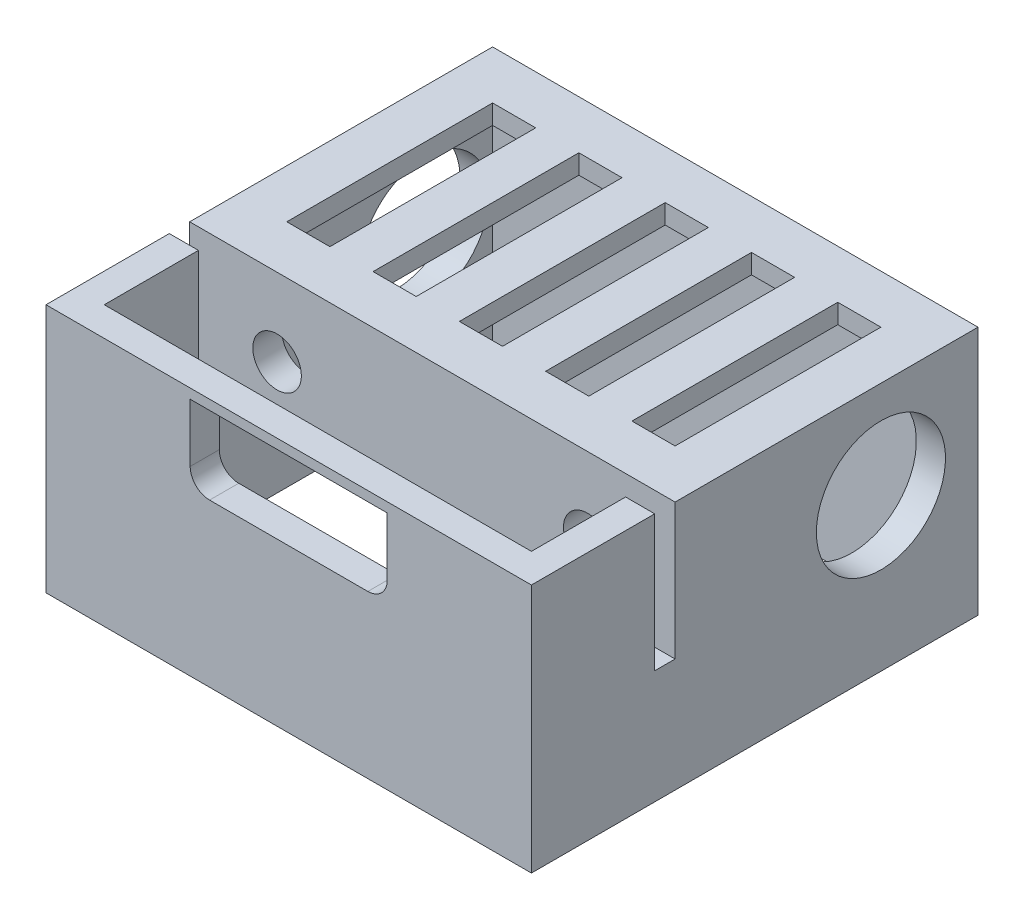
SolidWorks part; units mm, degrees
ref_plane "Alzado" through (0, 0, 0) normal (0, 0, 1) x (1, 0, 0)
ref_plane "Planta" through (0, 0, 0) normal (0, 1, 0) x (1, 0, 0)
ref_plane "Vista lateral" through (0, 0, 0) normal (1, 0, 0) x (0, 0, -1)
sketch "Croquis1" plane through (0, 0, 0) normal (0, 1, 0) x (1, 0, 0)
  line L0 (3, 3) -> (-47, 3)
  line L1 (0, 0) -> (-44, 0)
  line L2 (0, 0) -> (0, -40)
  line L3 (0, -40) -> (-44, -40)
  line L4 (-44, 0) -> (-44, -40)
  line L5 (-47, 3) -> (-47, -43)
  line L6 (3, -43) -> (-47, -43)
  line L7 (3, 3) -> (3, -43)
  dimension "D1" = 44
  dimension "D2" = 40
  dimension "D3" = 3
extrude "Saliente-Extruir1" add sketch "Croquis1" along normal blind 15
sketch "Croquis4" plane through (0, 15, 0) normal (0, 1, 0) x (1, 0, 0)
  line L0 (-47, -43) -> (3, -43) construction
  line L1 (-44, -40) -> (0, -40)
  line L2 (-44, -40) -> (-44, -43)
  line L3 (-44, -43) -> (0, -43)
  line L4 (0, -40) -> (0, -43)
extrude "Saliente-Extruir3" add sketch "Croquis4" along normal blind 10.7
sketch "Croquis6" plane through (0, 0, 43) normal (0, 0, 1) x (1, 0, 0)
  line L0 (-22, 25.7) -> (-22, 24.7) construction
  line L1 (-44, 25.7) -> (0, 25.7) construction
  line L2 (-22, 24.7) -> (-11.85, 24.7)
  line L3 (-11.85, 24.7) -> (-11.85, 16.7)
  line L4 (-11.85, 16.7) -> (-32.15, 16.7)
  line L5 (-32.15, 16.7) -> (-32.15, 24.7)
  line L6 (-32.15, 24.7) -> (-22, 24.7)
  dimension "D1" = 1
  dimension "D2" = 10.15
  dimension "D3" = 10.15
  dimension "D4" = 8
extrude "Cortar-Extruir1" cut sketch "Croquis6" against normal up to next
sketch "Croquis7" plane through (0, 0, 43) normal (0, 0, 1) x (1, 0, 0)
  line L0 (-22, 25.7) -> (-22, 19.9995) construction
  line L1 (-47, 15) -> (-44, 15)
  line L2 (-47, 15) -> (-47, 25.7)
  line L3 (-47, 25.7) -> (-44, 25.7)
  line L4 (-44, 15) -> (-44, 25.7)
  line L5 (-44, 25.7) -> (0, 25.7) construction
  line L6 (0, 15) -> (0, 25.7)
  line L7 (3, 25.7) -> (0, 25.7)
  line L8 (3, 15) -> (3, 25.7)
  line L9 (3, 15) -> (0, 15)
extrude "Saliente-Extruir4" add sketch "Croquis7" against normal blind 10.7
sketch "Croquis8" plane through (0, 15, 0) normal (0, 1, 0) x (1, 0, 0)
  line L0 (-45.5, -32.3) -> (-45.5, -28.2) construction
  line L1 (-47, -28.2) -> (-44, -28.2)
  line L2 (0, -28.2) -> (3, -28.2)
  line L3 (-47, -32.3) -> (-44, -32.3) construction
  line L4 (1.5, -28.2) -> (1.5, -32.3) construction
  line L5 (0, -32.3) -> (3, -32.3) construction
  line L8 (0, 0) -> (0, -32.3)
  line L9 (0, -32.3) -> (3, -32.3)
  line L10 (3, -32.3) -> (3, 3)
  line L11 (3, 3) -> (-47, 3)
  line L12 (-47, 3) -> (-47, -32.3)
  line L13 (-47, -32.3) -> (-44, -32.3)
  line L14 (-44, -32.3) -> (-44, 0)
  line L15 (-44, 0) -> (0, 0)
  line L16 (0, 0) -> (0, -28.2)
  line L18 (3, -28.2) -> (3, 3)
  line L19 (3, 3) -> (-47, 3)
  line L20 (-47, 3) -> (-47, -28.2)
  line L22 (-44, -28.2) -> (-44, 0)
  line L23 (-44, 0) -> (0, 0)
  dimension "D2" = 4.1
  dimension "D3" = 4.1
  dimension "D1" = 0
extrude "Saliente-Extruir5" add sketch "Croquis8" along normal blind 10.7
sketch "Croquis9" plane through (-47, 0, 0) normal (-1, 0, 0) x (0, 0, 1)
  line L0 (-3, 15.7) -> (7, 15.7) construction
  line L1 (-3, 25.7) -> (-3, 0) construction
  line L2 (7, 15.7) -> (7, 25.7) construction
  line L3 (-3, 25.7) -> (28.2, 25.7) construction
  circle A0 centre (7, 15.7) radius 6.65
  dimension "D1" = 13.3
  dimension "D2" = 10
  dimension "D3" = 10
extrude "Cortar-Extruir2" cut sketch "Croquis9" against normal up to next
sketch "Croquis10" plane through (0, 0, 0) normal (-1, 0, 0) x (0, 0, 1)
  circle A0 centre (7, 15.7) radius 6.65 construction
  circle A1 centre (7, 15.7) radius 6.65
extrude "Cortar-Extruir3" cut sketch "Croquis10" against normal up to next
sketch "Croquis11" plane through (0, 25.7, 0) normal (0, 1, 0) x (1, 0, 0)
  line L0 (-47, 3) -> (-47, -28.2)
  line L1 (-47, 3) -> (3, 3)
  line L5 (-47, 3) -> (-47, -28.2) construction
  line L6 (-47, -28.2) -> (3, -28.2)
  line L7 (3, -28.2) -> (3, 3) construction
  line L8 (3, -28.2) -> (3, 3)
  dimension "D1" = 31.2
extrude "Saliente-Extruir6" add sketch "Croquis11" against normal blind 2
sketch "Croquis12" plane through (0, 0, 0) normal (-1, 0, 0) x (0, 0, 1)
  line L1 (28.2, 23.7) -> (25.2, 23.7)
  line L2 (28.2, 23.7) -> (28.2, 11.7)
  line L3 (28.2, 11.7) -> (25.2, 11.7)
  line L4 (25.2, 23.7) -> (25.2, 11.7)
  dimension "D1" = 3
  dimension "D2" = 12
extrude "Saliente-Extruir7" add sketch "Croquis12" along normal up to surface (44 mm away) up to face at (-44, 15.7, 0.35)
sketch "Croquis13" plane through (0, 0, 25.2) normal (0, 0, -1) x (-1, 0, 0)
  line L0 (0, 17.7) -> (6, 17.7) construction
  line L1 (0, 23.7) -> (0, 11.7) construction
  line L2 (22, 11.7) -> (22, 18.7495) construction
  line L3 (44, 11.7) -> (0, 11.7) construction
  line L4 (6, 17.7) -> (6, 23.7) construction
  line L5 (44, 23.7) -> (0, 23.7) construction
  circle A0 centre (6, 17.7) radius 2.5
  circle A1 centre (38, 17.7) radius 2.5
  dimension "D2" = 5
  dimension "D1" = 6
extrude "Cortar-Extruir4" cut sketch "Croquis13" against normal up to next
sketch "Croquis14" plane through (0, 0, 25.2) normal (0, 0, -1) x (-1, 0, 0)
  line L0 (44, 17.7) -> (38, 17.7) construction
  line L1 (44, 11.7) -> (44, 23.7) construction
  line L2 (22, 11.7) -> (22, 15.4) construction
  line L3 (43.3116, 17.7) -> (40.6558, 22.3)
  line L4 (40.6558, 22.3) -> (35.3442, 22.3)
  line L5 (35.3442, 22.3) -> (32.6884, 17.7)
  line L6 (32.6884, 17.7) -> (35.3442, 13.1)
  line L7 (35.3442, 13.1) -> (40.6558, 13.1)
  line L8 (40.6558, 13.1) -> (43.3116, 17.7)
  line L9 (44, 11.7) -> (0, 11.7) construction
  line L10 (3.3442, 13.1) -> (0.6884, 17.7)
  line L11 (8.6558, 13.1) -> (3.3442, 13.1)
  line L12 (11.3116, 17.7) -> (8.6558, 13.1)
  line L13 (8.6558, 22.3) -> (11.3116, 17.7)
  line L14 (3.3442, 22.3) -> (8.6558, 22.3)
  line L15 (0.6884, 17.7) -> (3.3442, 22.3)
  circle A0 centre (38, 17.7) radius 4.6 construction
  circle A1 centre (6, 17.7) radius 4.6 construction
  dimension "D1" = 9.2
fillet "Redondeo1" radius 2 2 edges at (-32.15, 16.7, 41.5) (-11.85, 16.7, 41.5)
sketch "Croquis15" plane through (-47, 0, 0) normal (-1, 0, 0) x (0, 0, 1)
  line L1 (32.3, 15) -> (30.3, 15)
  line L2 (32.3, 15) -> (32.3, 25.7)
  line L3 (32.3, 25.7) -> (30.3, 25.7)
  line L4 (30.3, 15) -> (30.3, 25.7)
  dimension "D1" = 2
extrude "Saliente-Extruir8" add sketch "Croquis15" against normal up to surface (3 mm away) up to face at (-44, 15.7, 0.35)
sketch "Croquis16" plane through (-47, 0, 0) normal (-1, 0, 0) x (0, 0, 1)
  line L1 (28.2, 15) -> (30.3, 15)
  line L2 (28.2, 15) -> (28.2, 11.7)
  line L3 (28.2, 11.7) -> (30.3, 11.7)
  line L4 (30.3, 15) -> (30.3, 11.7)
  dimension "D1" = 3.3
extrude "Cortar-Extruir5" cut sketch "Croquis16" against normal up to surface (50 mm away) up to face at (3, 16.6, 25.125)
sketch "Croquis17" plane through (3, 0, 0) normal (1, 0, 0) x (0, 0, -1)
  line L1 (-32.3, 25.7) -> (-30.3, 25.7)
  line L2 (-32.3, 25.7) -> (-32.3, 15)
  line L3 (-32.3, 15) -> (-30.3, 15)
  line L4 (-30.3, 25.7) -> (-30.3, 15)
extrude "Saliente-Extruir9" add sketch "Croquis17" against normal up to surface (3 mm away) up to face at (0, 14.9, 25.8)
sketch "Croquis18" plane through (0, 23.7, 0) normal (0, -1, 0) x (1, 0, 0)
  line L4 (-37.5556, 23.2) -> (-37.5556, 2)
  line L5 (-33.1111, 23.2) -> (-33.1111, 2)
  line L6 (-28.6667, 23.2) -> (-28.6667, 2)
  line L7 (-24.2222, 23.2) -> (-24.2222, 2)
  line L8 (-2, 23.2) -> (-42, 23.2)
  line L9 (-42, 23.2) -> (-42, 2)
  line L10 (-42, 2) -> (-2, 2)
  line L11 (-2, 2) -> (-2, 23.2)
  line L12 (-2, 23.2) -> (-6.4444, 23.2)
  line L13 (-42, 23.2) -> (-42, 2)
  line L14 (-42, 2) -> (-37.5556, 2)
  line L15 (-2, 2) -> (-2, 23.2)
  line L16 (-19.7778, 23.2) -> (-19.7778, 2)
  line L17 (-15.3333, 23.2) -> (-15.3333, 2)
  line L18 (-10.8889, 23.2) -> (-10.8889, 2)
  line L19 (-6.4444, 23.2) -> (-6.4444, 2)
  line L20 (-2, 23.2) -> (-2, 2)
  line L21 (-42, 23.2) -> (-37.5556, 23.2) construction
  line L22 (-37.5556, 23.2) -> (-42, 23.2)
  line L23 (-28.6667, 23.2) -> (-33.1111, 23.2)
  line L24 (-19.7778, 23.2) -> (-24.2222, 23.2)
  line L25 (-10.8889, 23.2) -> (-15.3333, 23.2)
  line L26 (-6.4444, 2) -> (-2, 2)
  line L27 (-15.3333, 2) -> (-10.8889, 2)
  line L28 (-24.2222, 2) -> (-19.7778, 2)
  line L29 (-33.1111, 2) -> (-28.6667, 2)
  dimension "D3" = 4.4444
  dimension "D1" = 2
  dimension "D2" = 10
extrude "Cortar-Extruir6" cut sketch "Croquis18" against normal up to next contours L4 L22 L13 L14 | L5 L29 L6 L23 | L7 L28 L16 L24 | L17 L27 L18 L25 | L19 L26 L15 L12
